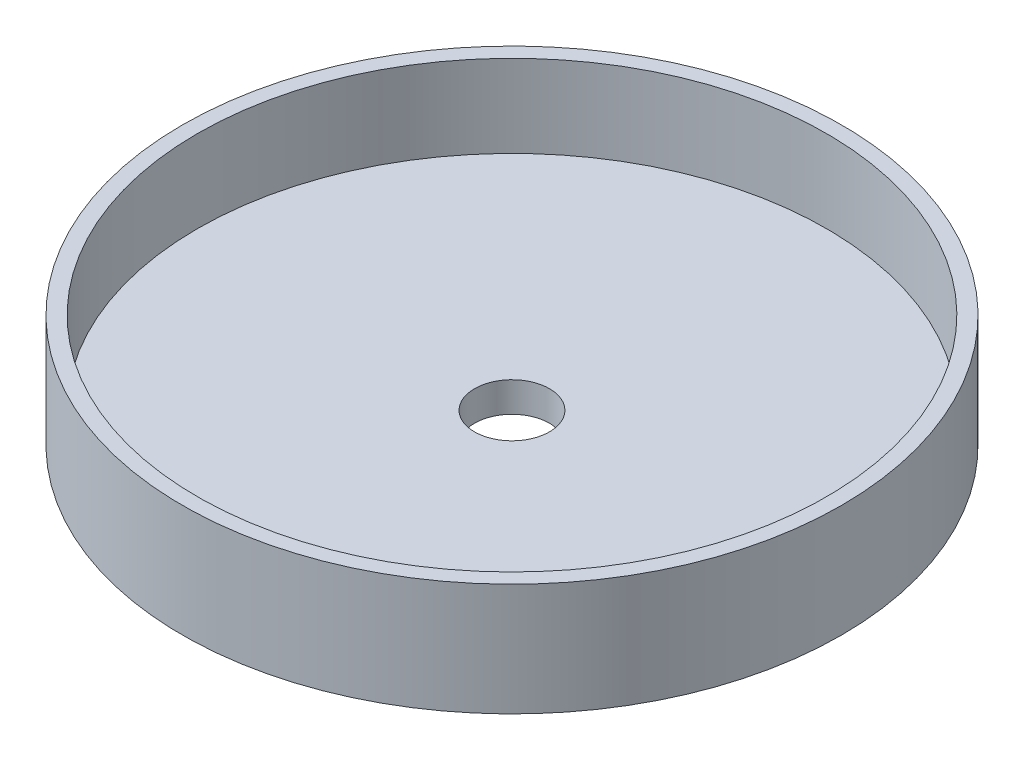
SolidWorks part; units mm, degrees
ref_plane "Front Plane" through (0, 0, 0) normal (0, 0, 1) x (1, 0, 0)
ref_plane "Top Plane" through (0, 0, 0) normal (0, 1, 0) x (1, 0, 0)
ref_plane "Right Plane" through (0, 0, 0) normal (1, 0, 0) x (0, 0, -1)
sketch "Sketch1" plane through (0, 0, 0) normal (0, 0, 1) x (1, 0, 0)
  line L0 (5, 0) -> (5, 4)
  line L1 (0, 0) -> (44, 0)
  line L2 (44, 0) -> (44, 15)
  line L3 (44, 15) -> (42, 15)
  line L4 (42, 15) -> (42, 4)
  line L5 (42, 4) -> (0, 4)
  line L6 (0, 4) -> (0, 0)
  dimension "D1" = 42
  dimension "D2" = 2
  dimension "D3" = 15
  dimension "D4" = 5
  dimension "D5" = 4
revolve "Revolve1" add sketch "Sketch1" angle 360 about L6
